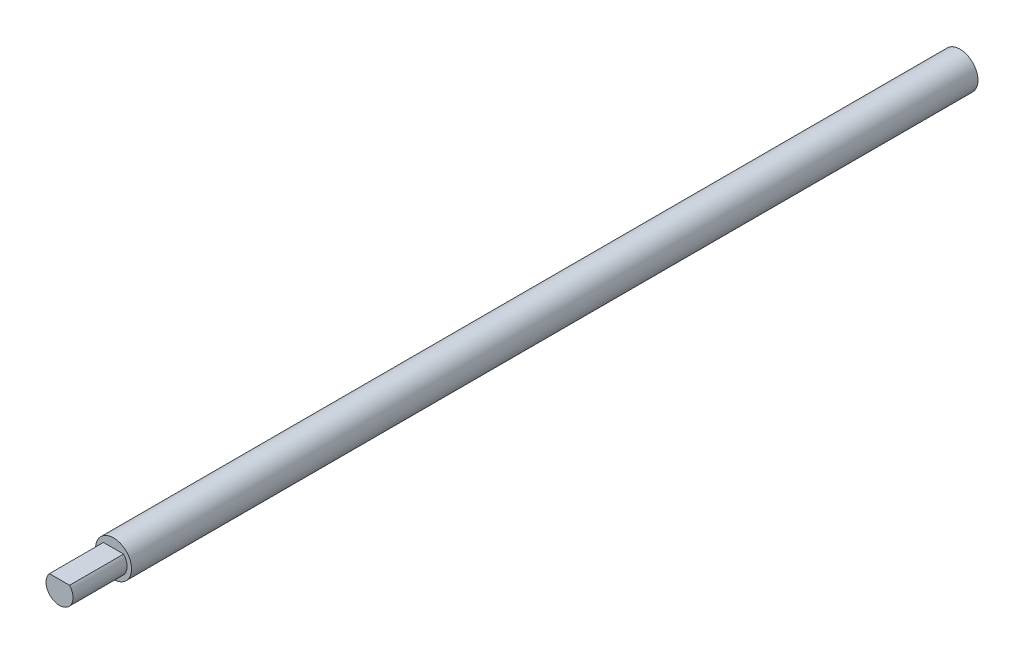
SolidWorks part; units mm, degrees
material "Barra Redonda SAE 1020 - 1/2\""
ref_plane "Plano frontal" through (0, 0, 0) normal (0, 0, 1) x (1, 0, 0)
ref_plane "Plano superior" through (0, 0, 0) normal (0, 1, 0) x (1, 0, 0)
ref_plane "Plano direito" through (0, 0, 0) normal (1, 0, 0) x (0, 0, -1)
sketch "Esboço1" plane through (0, 0, 0) normal (0, 0, 1) x (1, 0, 0)
  circle A0 centre (0, 0) radius 6.35
  dimension "D1" = 12.7
extrude "Ressalto-extrusão1" add sketch "Esboço1" along normal blind 200
sketch "Esboço2" plane through (0, 0, 200) normal (0, 0, 1) x (1, 0, 0)
  circle A0 centre (0, 0) radius 4
  circle A1 centre (0, 0) radius 12.7
  dimension "D1" = 8
  dimension "D2" = 25.4
extrude "Corte-extrusão1" cut sketch "Esboço2" against normal through all
sketch "Esboço3" plane through (0, 0, 0) normal (1, 0, 0) x (0, 0, -1)
  line L0 (-200, 4) -> (-200, -4) construction
  line L1 (-200, 2) -> (-188, 2)
  line L2 (-200, 2) -> (-200, 12)
  line L3 (-200, 12) -> (-188, 12)
  line L4 (-188, 2) -> (-188, 12)
  line L5 (-200, 0) -> (-121.987, 0) construction
  dimension "D1" = 12
  dimension "D2" = 10
  dimension "D3" = 2
extrude "Corte-extrusão2" cut sketch "Esboço3" against normal through all and the other way through all
sketch "Esboço5" plane through (0, 0, 0) normal (1, 0, 0) x (0, 0, -1)
  line L0 (0, 0) -> (-120.5536, 0) construction
  line L2 (-200, 2) -> (-200, -4) construction
  line L3 (-200, 3) -> (-188, 3)
  line L4 (-200, 3) -> (-200, 13)
  line L5 (-200, 13) -> (-188, 13)
  line L7 (-188, 3) -> (-188, 13)
  line L8 (-188, 4) -> (-188, 2) construction
  dimension "D1" = 10
  dimension "D2" = 6
revolve "Corte-Revolução2" cut sketch "Esboço5" angle 360 about L0
